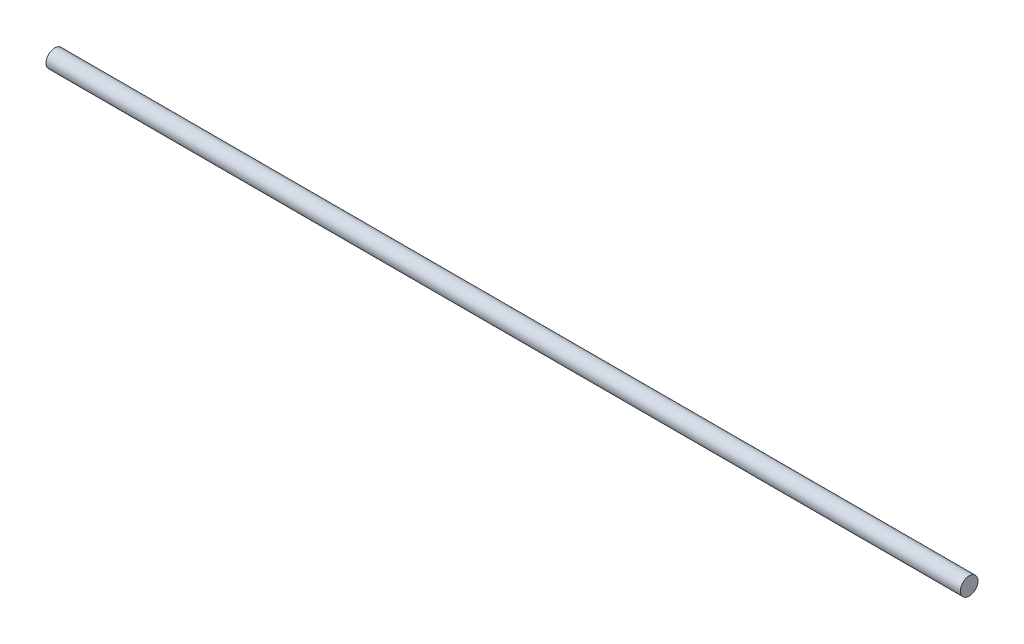
SolidWorks part; units mm, degrees
ref_plane "Front Plane" through (0, 0, 0) normal (0, 0, 1) x (1, 0, 0)
ref_plane "Top Plane" through (0, 0, 0) normal (0, 1, 0) x (1, 0, 0)
ref_plane "Right Plane" through (0, 0, 0) normal (1, 0, 0) x (0, 0, -1)
sketch "Sketch1" plane through (0, 0, 0) normal (1, 0, 0) x (0, 0, -1)
  circle A0 centre (0, 0) radius 3.175
extrude "Boss-Extrude1" add sketch "Sketch1" along normal blind 330.2
